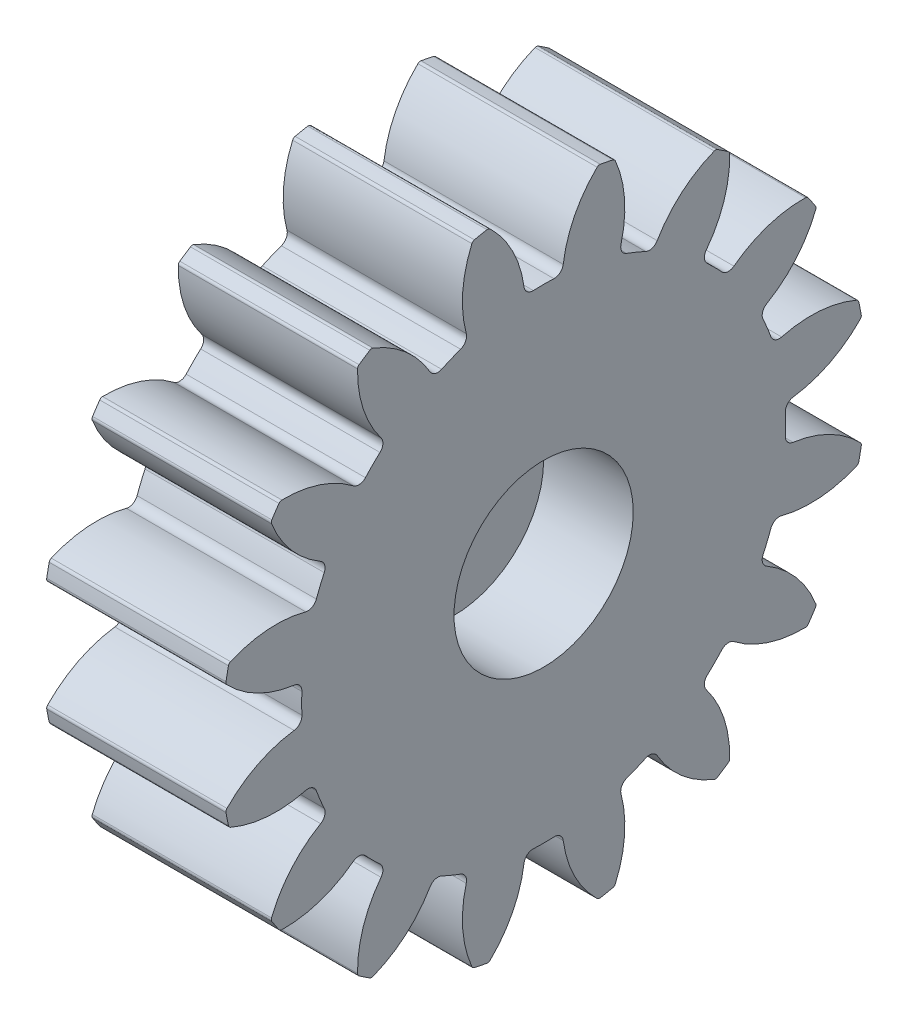
SolidWorks part; units mm, degrees
ref_plane "Plane1" through (0, 0, 0) normal (0, 0, 1) x (1, 0, 0)
ref_plane "Plane2" through (0, 0, 0) normal (0, 1, 0) x (1, 0, 0)
ref_plane "Plane3" through (0, 0, 0) normal (1, 0, 0) x (0, 0, -1)
sketch "HoldingSke" plane through (0, 0, 0) normal (0, 1, 0) x (1, 0, 0)
  line L0 (0, 0) -> (0.9613, -0.2756)
  line L1 (-15, 0) -> (100, 0) construction
  line L2 (0, 0) -> (-2.1039, 2.3779)
  line L3 (0, 0) -> (-11.863, 4.5341)
  line L4 (0, 0) -> (8.3015, 2.3804)
  line L5 (0, 0) -> (-46.8476, -17.4728)
  line L6 (0, 0) -> (-4.1448, -2.7965)
  line L7 (-2.1039, 2.3779) -> (8.6586, 51.2059)
  line L8 (-76.2, 54.61) -> (-75.9, 54.61)
  line L9 (-71.009, 38.7566) -> (-53.1078, 45.2721)
  line L10 (-76.2, 71.12) -> (104.1128, 71.12)
  line L11 (0, 0) -> (-5, 0)
  line L12 (-76.2, 101.6) -> (-76.162, 101.6)
  line L13 (24.9733, 27.94) -> (52.9518, 28.4284)
  line L14 (24.9733, 27.94) -> (24.9743, 27.94)
  line L15 (24.9733, 27.94) -> (100.4006, 29.5858)
  line L16 (-63.627, -1) -> (-12.827, -1)
  circle A0 centre (0, 0) radius 1
  circle A1 centre (0, 0) radius 6.749
  circle A2 centre (0, 0) radius 37.5
  circle A3 centre (0, 0) radius 1
  dimension "MHD" = 13.498
  dimension "Hub_dia" = 75
  dimension "Bore" = 2
  dimension "MBD" = 2
  dimension "Num_teeth" = 16
  dimension "Pitch" = 1
  dimension "Overall_len" = 50
  dimension "Show_teeth" = 16
  dimension "Thickness" = 5
  dimension "OAL" = 50.0001
  dimension "T_dim" = 0.3
  dimension "Ap" = 20
  dimension "H" = 19.05
  dimension "Pitch_radius" = 180.3128
  dimension "Width" = 5
  dimension "Backlash" = 0.038
  dimension "Addendum_fac" = 1
  dimension "Dedendum_fac" = 1.25
  dimension "Clearance_fac" = 0.25
  dimension "Dedendum_add" = 0.001
  dimension "Module" = 1
sketch "BasProSke" plane through (0, 0, 0) normal (0, 1, 0) x (1, 0, 0)
  line L0 (-10, 0) -> (60, 0) construction
  line L1 (0, 0) -> (0, 9)
  line L2 (0, 0) -> (5, 0)
  line L3 (5, 0) -> (5, 9)
  line L4 (5, 9) -> (0, 9)
  dimension "Thickness" = 5
  dimension "Diameter" = 18
revolve "Base-Revolve" add sketch "BasProSke" angle 360 about L0
sketch "TooCutSke" plane through (0, 0, 0) normal (1, 0, 0) x (0, 0, -1)
  line L1 (0, 0) -> (0, 107) construction
  line L2 (0, 0) -> (-0.8506, 7.9547) construction
  line L3 (0, 0) -> (-3.1089, 15.6293) construction
  line L4 (-0.8506, 7.9547) -> (-1.5544, 7.8146) construction
  arc A0 (0.5238, 6.7286) -> (-0.5238, 6.7286) centre (0, 0) ccw
  arc A1 (1.5534, 8.8907) -> (-1.5534, 8.8907) centre (0, 0) ccw
  circle A2 centre (0, 0) radius 8 construction
  circle A3 centre (0, 0) radius 7.5175 construction
  arc A4 (-0.5238, 6.7286) -> (-1.5534, 8.8907) centre (-3.7179, 6.5338) ccw
  arc A5 (1.5534, 8.8907) -> (0.5238, 6.7286) centre (3.7179, 6.5338) ccw
  dimension "Root_dia" = 13.498
  dimension "Overcut_dia" = 18.0508
  dimension "Pitch_dia" = 16
  dimension "Base_dia" = 15.0351
  dimension "Flank_rad" = 3.2
  dimension "Half_ang" = 11.25
  dimension "Half_CT" = 0.7176
extrude "ToothCut" cut sketch "TooCutSke" along normal through all
fillet "Breaks" radius 0.1 2 edges at (2.5, 8.869, -1.5299) (2.5, 8.869, 1.5299)
fillet "RootFillets" radius 0.251 2 edges at (2.5, 6.7286, -0.5238) (2.5, 6.7286, 0.5238)
pattern_circular "TeethCuts" count 16 every 22.5 about axis through (-10, 0, 0) along (1, 0, 0) of "ToothCut", "RootFillets", "Breaks"
sketch "HubNeaOneSke" plane through (0, 0, 0) normal (-1, 0, 0) x (0, 0, 1)
  circle A0 centre (0, 0) radius 6.749
  dimension "Diameter" = 13.498
extrude "HubNearOne" [suppressed] add sketch "HubNeaOneSke" along normal blind 45.0001
sketch "HubNeaBotSke" plane through (0, 0, 0) normal (-1, 0, 0) x (0, 0, 1)
  circle A0 centre (0, 0) radius 6.749
  dimension "Diameter" = 13.498
extrude "HubNearBoth" [suppressed] add sketch "HubNeaBotSke" along normal blind 22.5
ref_plane "FarPln" through (5, 0, 0) normal (1, 0, 0) x (0, 0, -1)
sketch "HubFarSke" plane through (5, 0, 0) normal (1, 0, 0) x (0, 0, -1)
  circle A0 centre (0, 0) radius 6.749
  dimension "Diameter" = 13.498
extrude "HubFar" [suppressed] add sketch "HubFarSke" along normal blind 22.5
sketch "BorSke" plane through (0, 0, 0) normal (1, 0, 0) x (0, 0, -1)
  circle A0 centre (0, 0) radius 1
  dimension "Diameter" = 2
extrude "Bore" cut sketch "BorSke" along normal mid plane 100.0001
sketch "KeySke" plane through (0, 0, 0) normal (1, 0, 0) x (0, 0, -1)
  line L0 (-0.4, 0) -> (-0.4, 1.3)
  line L1 (-0.4, 1.3) -> (0.4, 1.3)
  line L2 (0.4, 1.3) -> (0.4, 0)
  line L3 (0, 0) -> (0, 34) construction
  line L4 (-0.4, 0) -> (0.4, 0)
  dimension "Offset" = 1.3
  dimension "Width" = 0.8
extrude "Keyway" [suppressed] cut sketch "KeySke" along normal mid plane 100.0001
pattern_circular "Keyway2" [suppressed] count 2 every 90 about axis through (-10, 0, 0) along (1, 0, 0)
sketch "Szkic1" plane through (5, 0, 0) normal (1, 0, 0) x (0, 0, -1)
  circle A0 centre (0, 0) radius 2.5
  dimension "D1" = 5
extrude "Wytnij-wyciągnięcie1" cut sketch "Szkic1" against normal blind 2.5
sketch "Szkic2" plane through (0, 0, 0) normal (-1, 0, 0) x (0, 0, 1)
  circle A0 centre (0, 0) radius 2
  dimension "D1" = 4
extrude "Wytnij-wyciągnięcie2" cut sketch "Szkic2" against normal blind 1
equation "' \"Module@HoldingSke\" = 6.35"
equation "' \"Num_teeth@HoldingSke\" = 12"
equation "' \"Ap@HoldingSke\" =  20"
equation "' \"Ap@HoldingSke\" = 20"
equation "' \"Width@HoldingSke\" = 0.5 * 25.4"
equation "' \"Hub_dia@HoldingSke\"= 1 * 25.4"
equation "' \"Hub_dia@HoldingSke\" = 1 * 25.4"
equation "' \"Overall_len@HoldingSke\" = 1.0 * 25.4"
equation "' \"Bore@HoldingSke\" = 0.75 * 25.4"
equation "' \"T_dim@HoldingSke\" = 0.1 * 25.4"
equation "' \"Width@KeySke\" = 0.25 * 25.4"
equation "' \"Show_teeth@HoldingSke\" = 13"
equation "' \"Backlash@HoldingSke\" = 0.009 * 25.4"
equation "' \"Addendum_fac@HoldingSke\" = 1.0"
equation "' \"Dedendum_fac@HoldingSke\" = 1.25"
equation "' \"Dedendum_add@HoldingSke\" = 0.00005 * 25.4"
equation "' \"Clearance_fac@HoldingSke\" = 0.25"
equation "\"Pitch@HoldingSke\" = 1 / \"Module@HoldingSke\""
equation "\"Overcut_dia@TooCutSke\" = (\"Num_teeth@HoldingSke\" + 2 * \"Addendum_fac@HoldingSke\") / \"Pitch@HoldingSke\" + 0.002 * 25.4"
equation "\"Pitch_dia@TooCutSke\" = \"Num_teeth@HoldingSke\" / \"Pitch@HoldingSke\""
equation "\"Base_dia@TooCutSke\" = \"Num_teeth@HoldingSke\" / \"Pitch@HoldingSke\" * cos((\"Ap@HoldingSke\"  * 3.14159265 / 180))"
equation "\"Root_dia@TooCutSke\" = (\"Num_teeth@HoldingSke\" + 2) / \"Pitch@HoldingSke\" - 2 * (\"Addendum_fac@HoldingSke\" + \"Dedendum_fac@HoldingSke\") / \"Pitch@HoldingSke\" - \"Dedendum_add@HoldingSke\" * 2"
equation "\"Half_ang@TooCutSke\" = 180 / \"Num_teeth@HoldingSke\""
equation "\"Half_CT@TooCutSke\" = \"Num_teeth@HoldingSke\" / \"Pitch@HoldingSke\" * sin((3.14159265 / 2 / \"Num_teeth@HoldingSke\")) / 2 - 7 * \"Backlash@HoldingSke\" / 4"
equation "\"Flank_rad@TooCutSke\" = \"Num_teeth@HoldingSke\" / \"Pitch@HoldingSke\" / 5"
equation "\"Radius@RootFillets\" = \"Clearance_fac@HoldingSke\" / \"Pitch@HoldingSke\" + \"Dedendum_add@HoldingSke\""
equation "\"Thickness@HoldingSke\" = \"Width@HoldingSke\""
equation "\"OAL@HoldingSke\" = \"Thickness@HoldingSke\""
equation "\"MHD@HoldingSke\" = (\"Num_teeth@HoldingSke\" + 2) / \"Pitch@HoldingSke\" - 2 * (\"Addendum_fac@HoldingSke\" + \"Dedendum_fac@HoldingSke\")  / \"Pitch@HoldingSke\" - \"Dedendum_add@HoldingSke\" * 2"
equation "\"MBD@HoldingSke\" = (\"Num_teeth@HoldingSke\" + 2) / \"Pitch@HoldingSke\" - 2 * (\"Addendum_fac@HoldingSke\" + \"Dedendum_fac@HoldingSke\")  / \"Pitch@HoldingSke\" - \"Dedendum_add@HoldingSke\" * 2 - 0.002 * 25.4"
equation "\"MHD@HoldingSke\" = ((sgn( \"MHD@HoldingSke\" - \"Hub_dia@HoldingSke\" )-1)*( \"MHD@HoldingSke\" - \"Hub_dia@HoldingSke\" ))/-2+ \"Hub_dia@HoldingSke\""
equation "\"MBD@HoldingSke\" = ((sgn( \"MBD@HoldingSke\" - \"Bore@HoldingSke\" )-1)*( \"MBD@HoldingSke\" - \"Bore@HoldingSke\" ))/-2+ \"Bore@HoldingSke\""
equation "\"OAL@HoldingSke\" = ((sgn( \"OAL@HoldingSke\" - \"Overall_len@HoldingSke\" )+1)*( \"OAL@HoldingSke\" - \"Overall_len@HoldingSke\" ))/2 + \"Overall_len@HoldingSke\" + 0.000002 * 25.4"
equation "\"Num_teeth@TeethCuts\" = int( \"Show_teeth@HoldingSke\" ) + 1"
equation "\"Num_teeth@TeethCuts\" = ((sgn( \"Num_teeth@TeethCuts\" - \"Num_teeth@HoldingSke\" )-1)*( \"Num_teeth@TeethCuts\" - \"Num_teeth@HoldingSke\" ))/-2+ \"Num_teeth@HoldingSke\""
equation "\"Num_teeth@TeethCuts\" = ((sgn( \"Num_teeth@TeethCuts\" - 2.0)+1)*( \"Num_teeth@TeethCuts\" - 2.0))/2 +2.0"
equation "\"Angle@TeethCuts\" = 360.0 / \"Num_teeth@HoldingSke\""
equation "\"Diameter@BasProSke\" = (\"Num_teeth@HoldingSke\" + 2 * \"Addendum_fac@HoldingSke\") / \"Pitch@HoldingSke\""
equation "\"Thickness@BasProSke\"  = \"Thickness@HoldingSke\""
equation "' \"Fillet_rad@BasProSke\" =  \"Thickness@HoldingSke\" * 0.05"
equation "' \"Fillet_rad@BasProSke\" = \"Thickness@HoldingSke\" * 0.05"
equation "\"MHD@HoldingSke\" = ((sgn( \"MHD@HoldingSke\" - \"Root_dia@TooCutSke\" )-1)*( \"MHD@HoldingSke\" - \"Root_dia@TooCutSke\" ))/-2+ \"Root_dia@TooCutSke\""
equation "\"Diameter@HubNeaOneSke\" = \"MHD@HoldingSke\""
equation "\"Length@HubNearOne\" = \"OAL@HoldingSke\" - \"Thickness@BasProSke\""
equation "\"Diameter@HubNeaBotSke\" = \"MHD@HoldingSke\""
equation "\"Length@HubNearBoth\" = ( \"OAL@HoldingSke\" - \"Thickness@BasProSke\" ) / 2.0"
equation "\"Thickness@FarPln\" = \"Thickness@BasProSke\""
equation "\"Diameter@HubFarSke\" = \"MHD@HoldingSke\""
equation "\"Length@HubFar\" = ( \"OAL@HoldingSke\" - \"Thickness@BasProSke\" ) / 2.0"
equation "\"Diameter@BorSke\" = \"MBD@HoldingSke\""
equation "\"D1@Bore\" = \"OAL@HoldingSke\" * 2.0"
equation "\"D1@Keyway\" = \"OAL@HoldingSke\" * 2.0"
equation "\"Offset@KeySke\" = \"T_dim@HoldingSke\" + \"MBD@HoldingSke\" / 2.0"
